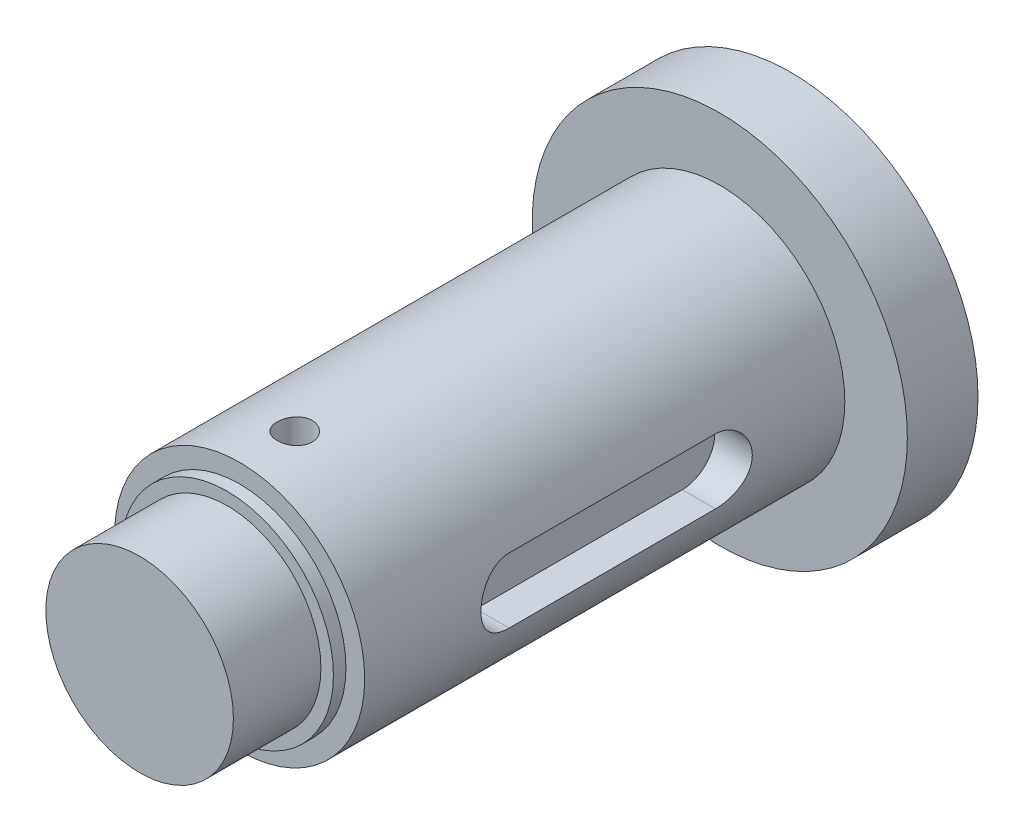
SolidWorks part; units mm, degrees
ref_plane "前视基准面" through (0, 0, 0) normal (0, 0, 1) x (1, 0, 0)
ref_plane "上视基准面" through (0, 0, 0) normal (0, 1, 0) x (1, 0, 0)
ref_plane "右视基准面" through (0, 0, 0) normal (1, 0, 0) x (0, 0, -1)
other "Configuration Table"
sketch "草图1" plane through (0, 0, 0) normal (0, 0, 1) x (1, 0, 0)
  circle A0 centre (0, 0) radius 15
  dimension "D1" = 30
extrude "凸台-拉伸1" add sketch "草图1" along normal blind 5.65
sketch "草图2" plane through (0, 0, 5.65) normal (0, 0, 1) x (1, 0, 0)
  circle A0 centre (0, 0) radius 10
  dimension "D1" = 20
extrude "凸台-拉伸2" add sketch "草图2" along normal blind 46.4
sketch "草图3" plane through (0, 0, 0) normal (0, 0, -1) x (-1, 0, 0)
  circle A0 centre (0, 0) radius 7 construction
  circle A1 centre (0, 7) radius 1.25
  circle A2 centre (7, 0) radius 1.25
  circle A3 centre (0, -7) radius 1.25
  circle A4 centre (-7, 0) radius 1.25
  point P14 (0, 0)
  dimension "D1" = 14
  dimension "D2" = 2.5
  dimension "D3" = 4
extrude "切除-拉伸1" cut sketch "草图3" against normal blind 10
sketch "草图4" plane through (0, 0, 52.05) normal (0, 0, 1) x (1, 0, 0)
  circle A0 centre (0, 0) radius 7.5
  dimension "D1" = 15
extrude "切除-拉伸2" cut sketch "草图4" against normal blind 7 flip side to cut
sketch "草图5" plane through (0, 0, 45.05) normal (0, 0, 1) x (1, 0, 0)
  circle A0 centre (0, 0) radius 8.5
  dimension "D1" = 17
extrude "切除-拉伸3" cut sketch "草图5" against normal blind 1 flip side to cut
ref_plane "基准面1" through (0, 10, 0) normal (0, 1, 0) x (1, 0, 0)
sketch "草图6" plane through (0, 10, 0) normal (0, 1, 0) x (1, 0, 0)
  line L0 (0, 5.7204) -> (0, -55.4139) construction
  line L1 (-10, -5.65) -> (10, -5.65) construction
  circle A0 centre (0, -39.65) radius 1.4
  dimension "D1" = 2.8
  dimension "D2" = 34
extrude "切除-拉伸4" cut sketch "草图6" against normal blind 8
mirror "镜向1" about plane through (0, 0, 0) normal (0, 1, 0) of "切除-拉伸4"
ref_plane "基准面2" through (10, 0, 0) normal (1, 0, 0) x (0, 0, -1)
sketch "草图7" plane through (10, 0, 0) normal (1, 0, 0) x (0, 0, -1)
  line L0 (-32.15, 0) -> (-15.65, 0) construction
  line L1 (-32.15, 2.6) -> (-15.65, 2.6)
  line L2 (-32.15, -2.6) -> (-15.65, -2.6)
  line L3 (-5.65, 10) -> (-5.65, -10) construction
  arc A0 (-32.15, 2.6) -> (-32.15, -2.6) centre (-32.15, 0) ccw
  arc A1 (-15.65, -2.6) -> (-15.65, 2.6) centre (-15.65, 0) ccw
  point P3 (-23.9, 0)
  dimension "D1" = 2.6
  dimension "D3" = 10
  dimension "D2" = 16.5
extrude "切除-拉伸5" cut sketch "草图7" against normal blind 3
